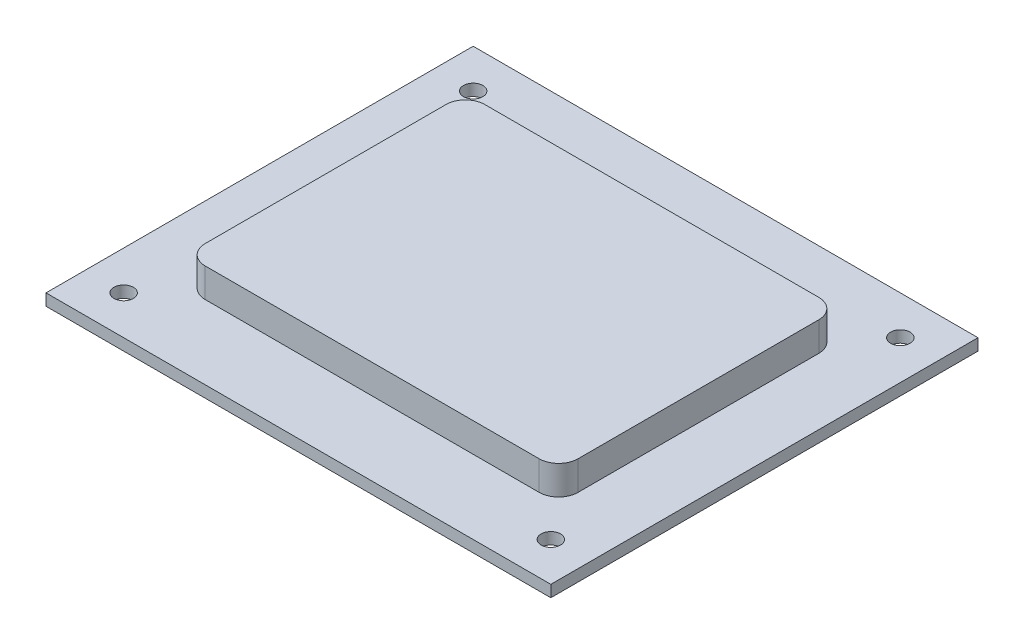
SolidWorks part; units mm, degrees
material "Custom Plastic"
ref_plane "Front Plane" through (0, 0, 0) normal (0, 0, 1) x (1, 0, 0)
ref_plane "Top Plane" through (0, 0, 0) normal (0, 1, 0) x (1, 0, 0)
ref_plane "Right Plane" through (0, 0, 0) normal (1, 0, 0) x (0, 0, -1)
sketch "Sketch1" plane through (0, 0, 0) normal (0, 1, 0) x (1, 0, 0)
  line L1 (-46.2831, 21.7817) -> (8.3269, 21.7817)
  line L2 (-49.4581, 18.6067) -> (-49.4581, -20.7633)
  line L3 (-46.2831, -23.9383) -> (8.3269, -23.9383)
  line L4 (11.5019, 18.6067) -> (11.5019, -20.7633)
  arc A0 (8.3269, 21.7817) -> (11.5019, 18.6067) centre (8.3269, 18.6067) cw
  arc A1 (11.5019, -20.7633) -> (8.3269, -23.9383) centre (8.3269, -20.7633) cw
  arc A2 (-49.4581, -20.7633) -> (-46.2831, -23.9383) centre (-46.2831, -20.7633) ccw
  arc A3 (-46.2831, 21.7817) -> (-49.4581, 18.6067) centre (-46.2831, 18.6067) ccw
  point P6 (11.5019, 21.7817)
  point P11 (-49.4581, -23.9383)
  point P14 (-49.4581, 21.7817)
  dimension "D3" = 3.175
  dimension "D1" = 45.72
  dimension "D2" = 60.96
extrude "Boss-Extrude1" add sketch "Sketch1" along normal blind 4.7625
sketch "Sketch3" plane through (0, 0, 0) normal (0, -1, 0) x (1, 0, 0)
  line L0 (-46.2831, 23.9383) -> (8.3269, 23.9383) construction
  line L1 (-60.2531, 36.0033) -> (22.2969, 36.0033)
  line L2 (-60.2531, 36.0033) -> (-60.2531, -33.8467)
  line L3 (-60.2531, -33.8467) -> (22.2969, -33.8467)
  line L4 (22.2969, 36.0033) -> (22.2969, -33.8467)
  line L5 (11.5019, 20.7633) -> (11.5019, -18.6067) construction
  dimension "D1" = 82.55
  dimension "D2" = 69.85
  dimension "D3" = 12.065
  dimension "D4" = 10.795
extrude "Boss-Extrude2" add sketch "Sketch3" along normal blind 1.905
sketch "Sketch4" plane through (0, 0, 0) normal (0, 1, 0) x (1, 0, 0)
  line L0 (-60.2531, -36.0033) -> (-60.2531, 33.8467) construction
  line L1 (-60.2531, 33.8467) -> (22.2969, 33.8467) construction
  line L2 (22.2969, 33.8467) -> (22.2969, -36.0033) construction
  line L3 (22.2969, -36.0033) -> (-60.2531, -36.0033) construction
  circle A0 centre (-53.9031, 27.4967) radius 1.5875
  circle A1 centre (15.9469, 27.4967) radius 1.5875
  circle A2 centre (15.9469, -29.6533) radius 1.5875
  circle A3 centre (-53.9031, -29.6533) radius 1.5875
  dimension "D9" = 3.175
  dimension "D10" = 3.175
  dimension "D11" = 3.175
  dimension "D12" = 3.175
  dimension "D1" = 6.35
  dimension "D2" = 6.35
  dimension "D3" = 6.35
  dimension "D4" = 6.35
  dimension "D5" = 6.35
  dimension "D6" = 6.35
  dimension "D7" = 6.35
  dimension "D8" = 6.35
extrude "Cut-Extrude1" cut sketch "Sketch4" against normal through all
